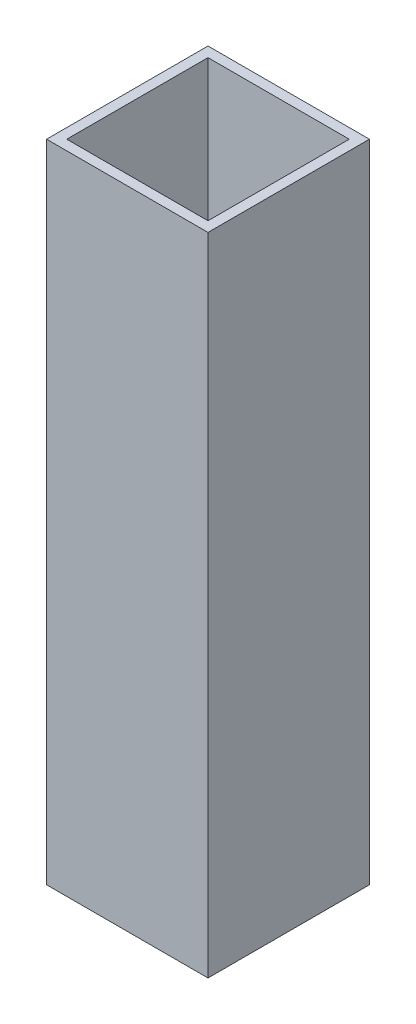
SolidWorks part; units mm, degrees
ref_plane "Front Plane" through (0, 0, 0) normal (0, 0, 1) x (1, 0, 0)
ref_plane "Top Plane" through (0, 0, 0) normal (0, 1, 0) x (1, 0, 0)
ref_plane "Right Plane" through (0, 0, 0) normal (1, 0, 0) x (0, 0, -1)
sketch "Sketch1" plane through (0, 0, 0) normal (0, 1, 0) x (1, 0, 0)
  line L1 (-12.7, -12.7) -> (12.7, -12.7)
  line L2 (-12.7, -12.7) -> (-12.7, 12.7)
  line L3 (-12.7, 12.7) -> (12.7, 12.7)
  line L4 (12.7, -12.7) -> (12.7, 12.7)
  line L7 (-11.1125, -11.1125) -> (11.1125, -11.1125)
  line L8 (-11.1125, -11.1125) -> (-11.1125, 11.1125)
  line L9 (-11.1125, 11.1125) -> (11.1125, 11.1125)
  line L10 (11.1125, -11.1125) -> (11.1125, 11.1125)
  point P6 (0, 0)
  dimension "D1" = 25.4
  dimension "D2" = 25.4
  dimension "D3" = 1.5875
  dimension "D4" = 1.5875
  dimension "D5" = 1.5875
extrude "Boss-Extrude1" add sketch "Sketch1" along normal blind 101.6
